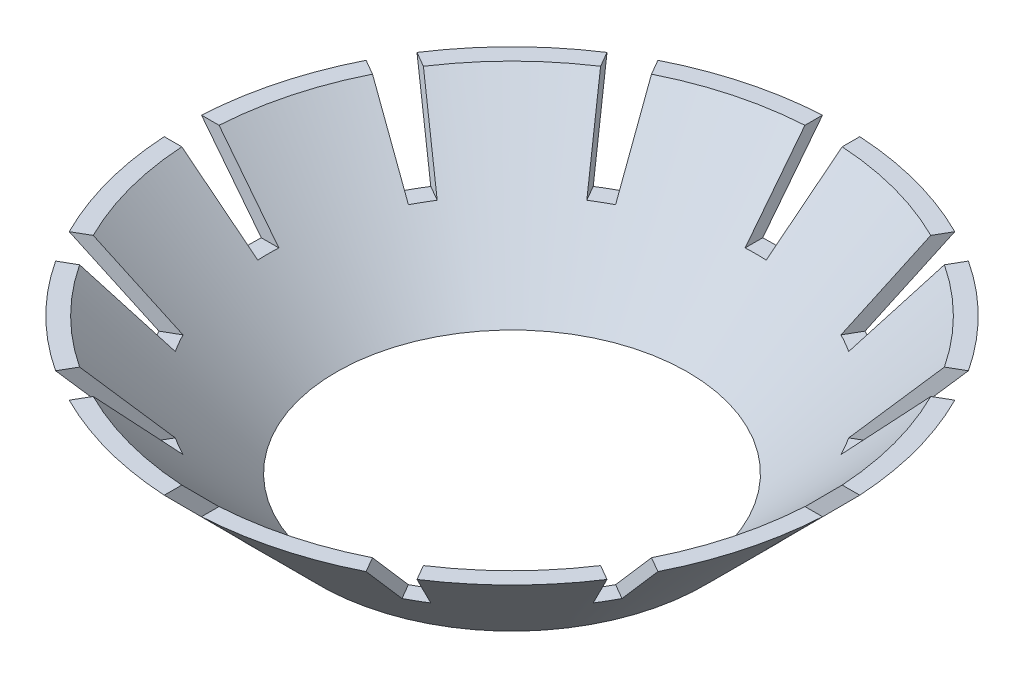
SolidWorks part; units mm, degrees
ref_plane "Plane1" through (0, 0, 0) normal (0, 0, 1) x (1, 0, 0)
ref_plane "Plane2" through (0, 0, 0) normal (0, 1, 0) x (1, 0, 0)
ref_plane "Plane3" through (0, 0, 0) normal (1, 0, 0) x (0, 0, -1)
sketch "Sketch1" plane through (0, 0, 0) normal (1, 0, 0) x (0, 0, -1)
  line L0 (0, -30) -> (0, 30) construction
  line L1 (8.5, 0) -> (15.1, 6.6)
  line L2 (8.5, 0) -> (9.3485, 0)
  line L3 (9.3485, 0) -> (15.9485, 6.6)
  line L4 (15.1, 6.6) -> (15.9485, 6.6)
  dimension "InsideDia" = 17
  dimension "D1" = 45
  dimension "OutsideDia" = 30.2
  dimension "Thickness" = 0.6
revolve "Base-Revolve" add sketch "Sketch1" angle 360 about L0
sketch "Sketch2" plane through (0, 0, 0) normal (0, 0, 1) x (1, 0, 0)
  line L0 (0, 3.3) -> (0, 7.6) construction
  line L1 (-0.51, 3.3) -> (0.51, 3.3)
  line L2 (0, -30) -> (0, 30) construction
  line L3 (-1.02, 7.6) -> (1.02, 7.6)
  line L4 (-0.51, 3.3) -> (-1.02, 7.6)
  line L5 (0.51, 3.3) -> (1.02, 7.6)
  dimension "D1" = 3.3
  dimension "D2" = 1.02
  dimension "D3" = 4.3
  dimension "D4" = 2.04
extrude "Cut-Extrude1" cut sketch "Sketch2" against normal through all
pattern_circular "CirPattern1" count 12 over 360 about axis through (0, 0, 0) along (0, 1, 0) of "Cut-Extrude1"
equation "\"D1@Sketch2\" =  ( \"OutsideDia@Sketch1\" - \"InsideDia@Sketch1\" )  / 4"
equation "\"D2@Sketch2\" = \"InsideDia@Sketch1\" * .06"
equation "\"D4@Sketch2\" = \"D2@Sketch2\" * 2"
equation "\"D3@Sketch2\" = \"D1@Sketch2\" + 1"
